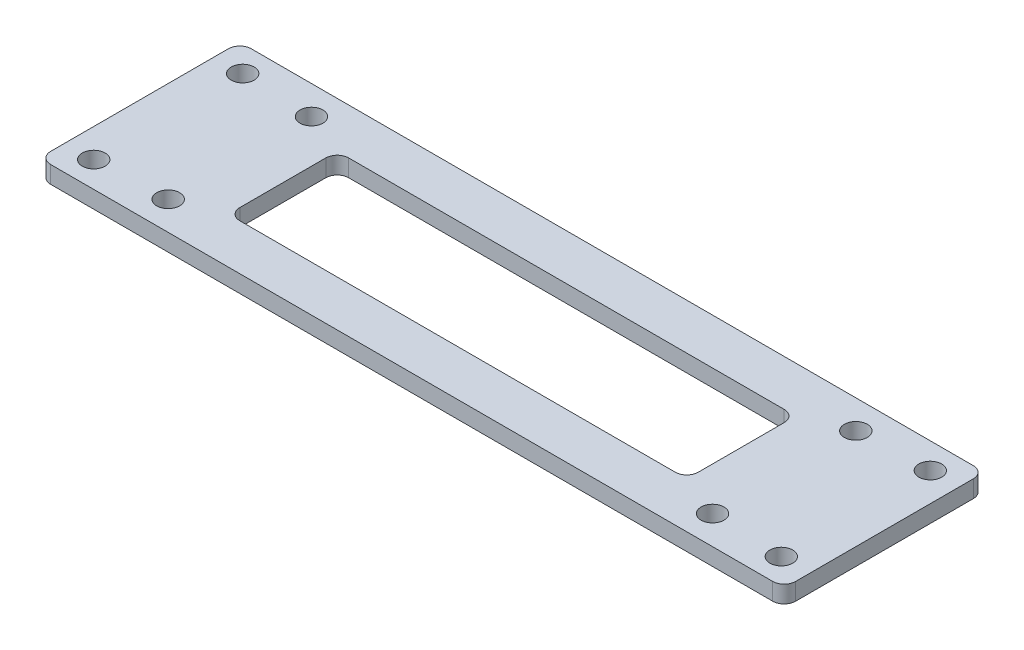
SolidWorks part; units mm, degrees
material "Thornel Mat VMA"
ref_plane "前视基准面" through (0, 0, 0) normal (0, 0, 1) x (1, 0, 0)
ref_plane "上视基准面" through (0, 0, 0) normal (0, 1, 0) x (1, 0, 0)
ref_plane "右视基准面" through (0, 0, 0) normal (1, 0, 0) x (0, 0, -1)
sketch "草图1" plane through (0, 0, 0) normal (0, 1, 0) x (1, 0, 0)
  line L0 (-47.5, 17.5) -> (-47.5, -17.5) construction
  line L1 (-55, 17.5) -> (55, 17.5)
  line L2 (-55, 17.5) -> (-55, -17.5)
  line L3 (-55, -17.5) -> (55, -17.5)
  line L4 (55, 17.5) -> (55, -17.5)
  line L5 (-55, 17.5) -> (55, -17.5) construction
  line L6 (-55, -17.5) -> (55, 17.5) construction
  line L7 (0, -55) -> (0, 55) construction
  circle A0 centre (-47.5, 12.5) radius 2
  circle A1 centre (-47.5, -12.5) radius 2
  circle A2 centre (47.5, -12.5) radius 2
  circle A3 centre (47.5, 12.5) radius 2
  point P0 (0, 0)
  dimension "D4" = 12.5
  dimension "D5" = 4
  dimension "D6" = 25
  dimension "D1" = 35
  dimension "D2" = 110
  dimension "D3" = 7.5
extrude "凸台-拉伸1" add sketch "草图1" along normal blind 3
sketch "草图2" plane through (0, 3, 0) normal (0, 1, 0) x (1, 0, 0)
  line L0 (55, 17.5) -> (-55, 17.5) construction
  line L6 (65, -17.5) -> (55, -17.5)
  line L7 (65, -17.5) -> (65, 17.5)
  line L8 (65, 17.5) -> (55, 17.5)
  line L9 (-65, -17.5) -> (-65, 17.5)
  line L10 (65, -17.5) -> (-65, 17.5) construction
  line L11 (65, 17.5) -> (-65, -17.5) construction
  line L12 (-55, 17.5) -> (-55, -17.5) construction
  line L13 (-55, 17.5) -> (-55, -17.5)
  line L14 (55, 17.5) -> (55, -17.5)
  line L15 (-55, 17.5) -> (-65, 17.5)
  line L16 (-55, -17.5) -> (-65, -17.5)
  line L17 (-60, 17.5) -> (-60, -17.5) construction
  line L18 (60, 17.5) -> (60, -17.5) construction
  circle A0 centre (-60, 13) radius 2
  circle A1 centre (60, 13) radius 2
  circle A2 centre (60, -13) radius 2
  circle A3 centre (-60, -13) radius 2
  point P0 (0, 0)
  point P2 (-60, -13)
  point P31 (0, 0)
  point P32 (60.2183, -13)
  point P33 (60, -13)
  dimension "D2" = 13
  dimension "D3" = 4
  dimension "D6" = 13
  dimension "D1" = 10
  dimension "D4" = 2
  dimension "D5" = 2
extrude "凸台-拉伸2" add sketch "草图2" against normal blind 3
sketch "草图3" plane through (0, 3, 0) normal (0, 1, 0) x (1, 0, 0)
  line L0 (65, 17.5) -> (-65, 17.5) construction
  line L1 (-40, 9.5) -> (40, 9.5)
  line L2 (-40, 9.5) -> (-40, -9.5)
  line L3 (-40, -9.5) -> (40, -9.5)
  line L4 (40, 9.5) -> (40, -9.5)
  line L5 (-40, 9.5) -> (40, -9.5) construction
  line L6 (-40, -9.5) -> (40, 9.5) construction
  circle A0 centre (47.5, 12.5) radius 2 construction
  point P0 (0, 0)
  dimension "D1" = 7.5
  dimension "D2" = 8
extrude "切除-拉伸1" cut sketch "草图3" against normal blind 3
fillet "圆角1" radius 2 8 edges at (-65, 1.5, -17.5) (-65, 1.5, 17.5) (65, 1.5, 17.5) (65, 1.5, -17.5) (-40, 1.5, 9.5) (40, 1.5, -9.5) (40, 1.5, 9.5) (-40, 1.5, -9.5)
